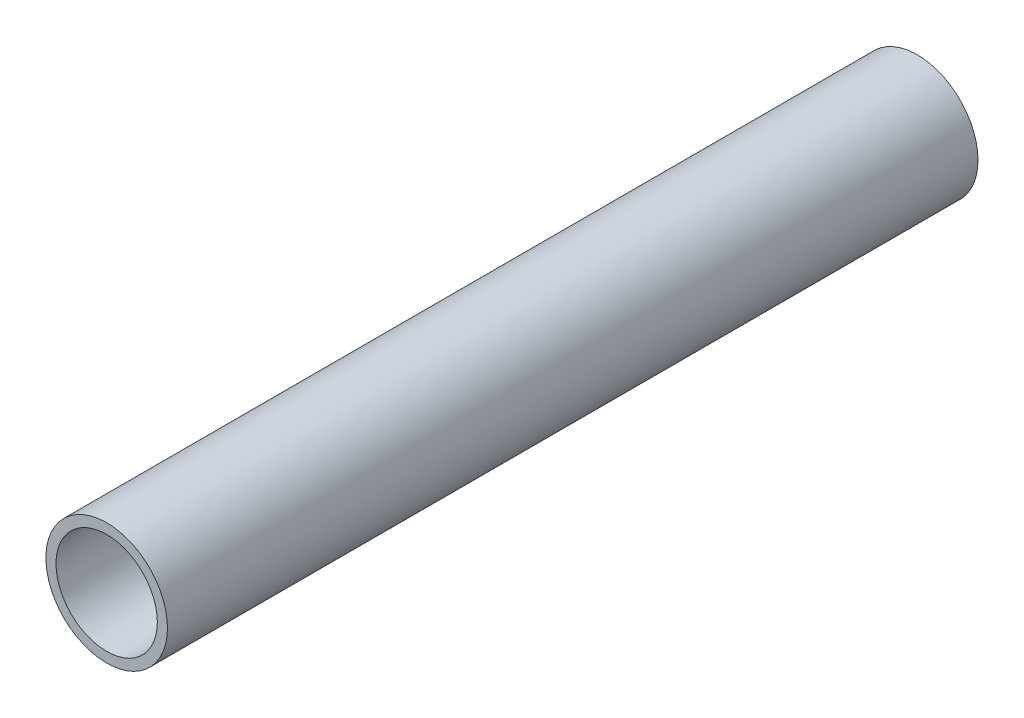
SolidWorks part; units mm, degrees
ref_plane "Front Plane" through (0, 0, 0) normal (0, 0, 1) x (1, 0, 0)
ref_plane "Top Plane" through (0, 0, 0) normal (0, 1, 0) x (1, 0, 0)
ref_plane "Right Plane" through (0, 0, 0) normal (1, 0, 0) x (0, 0, -1)
sketch "Sketch1" plane through (0, 0, 0) normal (0, 0, 1) x (1, 0, 0)
  circle A0 centre (0, 0) radius 15
  circle A1 centre (0, 0) radius 12.5
  dimension "D1" = 30
  dimension "D2" = 25
extrude "Boss-Extrude1" add sketch "Sketch1" along normal blind 200
